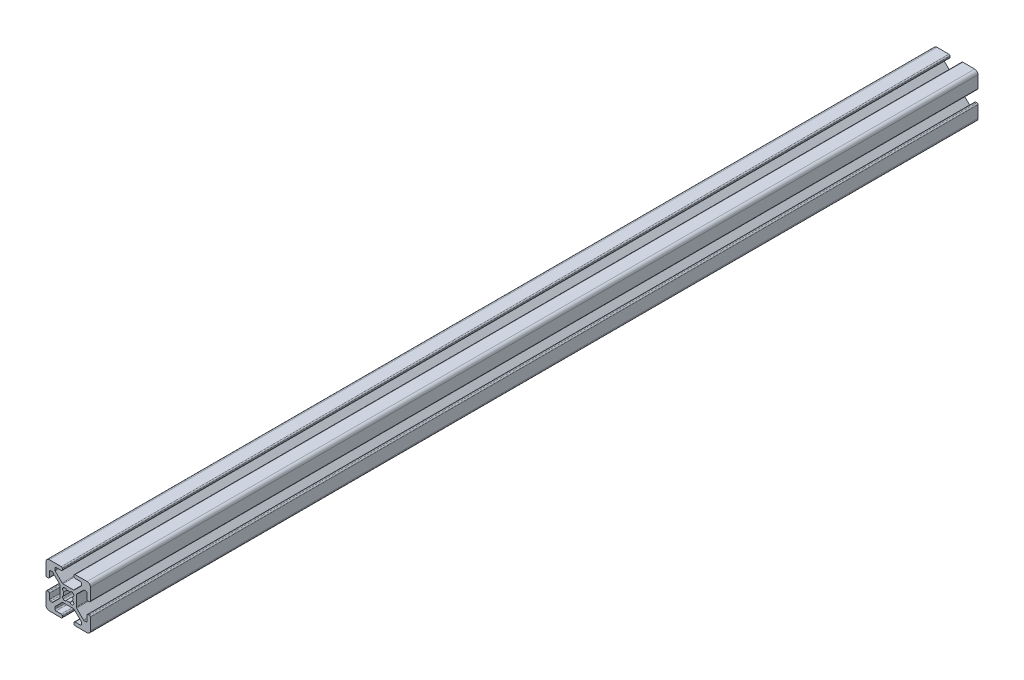
SolidWorks part; units mm, degrees
ref_plane "Front Plane" through (0, 0, 0) normal (0, 0, 1) x (1, 0, 0)
ref_plane "Top Plane" through (0, 0, 0) normal (0, 1, 0) x (1, 0, 0)
ref_plane "Right Plane" through (0, 0, 0) normal (1, 0, 0) x (0, 0, -1)
ref_plane "Plane1" through (0, 0, -400) normal (0, 0, -1) x (-1, 0, 0)
sketch "Sketch1" plane through (0, 0, -400) normal (0, 0, -1) x (-1, 0, 0)
  line L0 (10, -8.5) -> (10, -3.138)
  line L1 (9.492, -2.63) -> (9.008, -2.63)
  line L2 (8.5, -3.138) -> (8.5, -5.487)
  line L3 (7.992, -5.995) -> (7.2659, -5.995)
  line L4 (6.9067, -5.8462) -> (3.8038, -2.7433)
  line L5 (3.655, -2.3841) -> (3.655, 2.3838)
  line L6 (3.8038, 2.743) -> (6.907, 5.8462)
  line L7 (7.2662, 5.995) -> (7.992, 5.995)
  line L8 (8.5, 5.487) -> (8.5, 3.138)
  line L9 (9.008, 2.63) -> (9.492, 2.63)
  line L10 (10, 3.138) -> (10, 8.5)
  line L11 (8.5, 10) -> (3.138, 10)
  line L12 (2.63, 9.492) -> (2.63, 9.008)
  line L13 (3.138, 8.5) -> (5.487, 8.5)
  line L14 (5.995, 7.992) -> (5.995, 7.2659)
  line L15 (5.8462, 6.9067) -> (2.7433, 3.8038)
  line L16 (2.3841, 3.655) -> (-2.3838, 3.655)
  line L17 (-2.743, 3.8038) -> (-5.8462, 6.907)
  line L18 (-5.995, 7.2662) -> (-5.995, 7.992)
  line L19 (-5.487, 8.5) -> (-3.138, 8.5)
  line L20 (-2.63, 9.008) -> (-2.63, 9.492)
  line L21 (-3.138, 10) -> (-8.5, 10)
  line L22 (-10, 8.5) -> (-10, 3.138)
  line L23 (-9.492, 2.63) -> (-9.008, 2.63)
  line L24 (-8.5, 3.138) -> (-8.5, 5.487)
  line L25 (-7.992, 5.995) -> (-7.2659, 5.995)
  line L26 (-6.9067, 5.8462) -> (-3.8038, 2.7433)
  line L27 (-3.655, 2.3841) -> (-3.655, -2.3838)
  line L28 (-3.8038, -2.743) -> (-6.907, -5.8462)
  line L29 (-7.2662, -5.995) -> (-7.992, -5.995)
  line L30 (-8.5, -5.487) -> (-8.5, -3.138)
  line L31 (-9.008, -2.63) -> (-9.492, -2.63)
  line L32 (-10, -3.138) -> (-10, -8.5)
  line L33 (-8.5, -10) -> (-3.138, -10)
  line L34 (-2.63, -9.492) -> (-2.63, -9.008)
  line L35 (-3.138, -8.5) -> (-5.487, -8.5)
  line L36 (-5.995, -7.992) -> (-5.995, -7.2659)
  line L37 (-5.8462, -6.9067) -> (-2.7433, -3.8038)
  line L38 (-2.3841, -3.655) -> (2.3838, -3.655)
  line L39 (2.743, -3.8038) -> (5.8462, -6.907)
  line L40 (5.995, -7.2662) -> (5.995, -7.992)
  line L41 (5.487, -8.5) -> (3.138, -8.5)
  line L42 (2.63, -9.008) -> (2.63, -9.492)
  line L43 (3.138, -10) -> (8.5, -10)
  line L44 (2.3045, -2.1245) -> (2.1245, -2.3045)
  line L45 (-2.1245, -2.3045) -> (-2.3045, -2.1245)
  line L46 (-2.3045, 2.1245) -> (-2.1245, 2.3045)
  line L47 (2.1245, 2.3045) -> (2.3045, 2.1245)
  arc A0 (10, -3.138) -> (9.492, -2.63) centre (9.492, -3.138) ccw
  arc A1 (9.008, -2.63) -> (8.5, -3.138) centre (9.008, -3.138) ccw
  arc A2 (8.5, -5.487) -> (7.992, -5.995) centre (7.992, -5.487) cw
  arc A3 (7.2659, -5.995) -> (6.9067, -5.8462) centre (7.2659, -5.487) cw
  arc A4 (3.8038, -2.7433) -> (3.655, -2.3841) centre (4.163, -2.3841) cw
  arc A5 (3.655, 2.3838) -> (3.8038, 2.743) centre (4.163, 2.3838) cw
  arc A6 (6.907, 5.8462) -> (7.2662, 5.995) centre (7.2662, 5.487) cw
  arc A7 (7.992, 5.995) -> (8.5, 5.487) centre (7.992, 5.487) cw
  arc A8 (8.5, 3.138) -> (9.008, 2.63) centre (9.008, 3.138) ccw
  arc A9 (9.492, 2.63) -> (10, 3.138) centre (9.492, 3.138) ccw
  arc A10 (10, 8.5) -> (8.5, 10) centre (8.5, 8.5) ccw
  arc A11 (3.138, 10) -> (2.63, 9.492) centre (3.138, 9.492) ccw
  arc A12 (2.63, 9.008) -> (3.138, 8.5) centre (3.138, 9.008) ccw
  arc A13 (5.487, 8.5) -> (5.995, 7.992) centre (5.487, 7.992) cw
  arc A14 (5.995, 7.2659) -> (5.8462, 6.9067) centre (5.487, 7.2659) cw
  arc A15 (2.7433, 3.8038) -> (2.3841, 3.655) centre (2.3841, 4.163) cw
  arc A16 (-2.3838, 3.655) -> (-2.743, 3.8038) centre (-2.3838, 4.163) cw
  arc A17 (-5.8462, 6.907) -> (-5.995, 7.2662) centre (-5.487, 7.2662) cw
  arc A18 (-5.995, 7.992) -> (-5.487, 8.5) centre (-5.487, 7.992) cw
  arc A19 (-3.138, 8.5) -> (-2.63, 9.008) centre (-3.138, 9.008) ccw
  arc A20 (-2.63, 9.492) -> (-3.138, 10) centre (-3.138, 9.492) ccw
  arc A21 (-8.5, 10) -> (-10, 8.5) centre (-8.5, 8.5) ccw
  arc A22 (-10, 3.138) -> (-9.492, 2.63) centre (-9.492, 3.138) ccw
  arc A23 (-9.008, 2.63) -> (-8.5, 3.138) centre (-9.008, 3.138) ccw
  arc A24 (-8.5, 5.487) -> (-7.992, 5.995) centre (-7.992, 5.487) cw
  arc A25 (-7.2659, 5.995) -> (-6.9067, 5.8462) centre (-7.2659, 5.487) cw
  arc A26 (-3.8038, 2.7433) -> (-3.655, 2.3841) centre (-4.163, 2.3841) cw
  arc A27 (-3.655, -2.3838) -> (-3.8038, -2.743) centre (-4.163, -2.3838) cw
  arc A28 (-6.907, -5.8462) -> (-7.2662, -5.995) centre (-7.2662, -5.487) cw
  arc A29 (-7.992, -5.995) -> (-8.5, -5.487) centre (-7.992, -5.487) cw
  arc A30 (-8.5, -3.138) -> (-9.008, -2.63) centre (-9.008, -3.138) ccw
  arc A31 (-9.492, -2.63) -> (-10, -3.138) centre (-9.492, -3.138) ccw
  arc A32 (-10, -8.5) -> (-8.5, -10) centre (-8.5, -8.5) ccw
  arc A33 (-3.138, -10) -> (-2.63, -9.492) centre (-3.138, -9.492) ccw
  arc A34 (-2.63, -9.008) -> (-3.138, -8.5) centre (-3.138, -9.008) ccw
  arc A35 (-5.487, -8.5) -> (-5.995, -7.992) centre (-5.487, -7.992) cw
  arc A36 (-5.995, -7.2659) -> (-5.8462, -6.9067) centre (-5.487, -7.2659) cw
  arc A37 (-2.7433, -3.8038) -> (-2.3841, -3.655) centre (-2.3841, -4.163) cw
  arc A38 (2.3838, -3.655) -> (2.743, -3.8038) centre (2.3838, -4.163) cw
  arc A39 (5.8462, -6.907) -> (5.995, -7.2662) centre (5.487, -7.2662) cw
  arc A40 (5.995, -7.992) -> (5.487, -8.5) centre (5.487, -7.992) cw
  arc A41 (3.138, -8.5) -> (2.63, -9.008) centre (3.138, -9.008) ccw
  arc A42 (2.63, -9.492) -> (3.138, -10) centre (3.138, -9.492) ccw
  arc A43 (8.5, -10) -> (10, -8.5) centre (8.5, -8.5) ccw
  arc A44 (1.9358, 0.8037) -> (1.9358, -0.8037) centre (0, 0) cw
  arc A45 (1.9358, -0.8037) -> (2.3045, -2.1245) centre (1.748, -1.568) cw
  arc A46 (2.1245, -2.3045) -> (0.8037, -1.9358) centre (1.568, -1.748) cw
  arc A47 (0.8037, -1.9358) -> (-0.8037, -1.9358) centre (0, 0) cw
  arc A48 (-0.8037, -1.9358) -> (-2.1245, -2.3045) centre (-1.568, -1.748) cw
  arc A49 (-2.3045, -2.1245) -> (-1.9358, -0.8037) centre (-1.748, -1.568) cw
  arc A50 (-1.9358, -0.8037) -> (-1.9358, 0.8037) centre (0, 0) cw
  arc A51 (-1.9358, 0.8037) -> (-2.3045, 2.1245) centre (-1.748, 1.568) cw
  arc A52 (-2.1245, 2.3045) -> (-0.8037, 1.9358) centre (-1.568, 1.748) cw
  arc A53 (-0.8037, 1.9358) -> (0.8037, 1.9358) centre (0, 0) cw
  arc A54 (0.8037, 1.9358) -> (2.1245, 2.3045) centre (1.568, 1.748) cw
  arc A55 (2.3045, 2.1245) -> (1.9358, 0.8037) centre (1.748, 1.568) cw
extrude "Boss-Extrude1" add sketch "Sketch1" against normal blind 400
